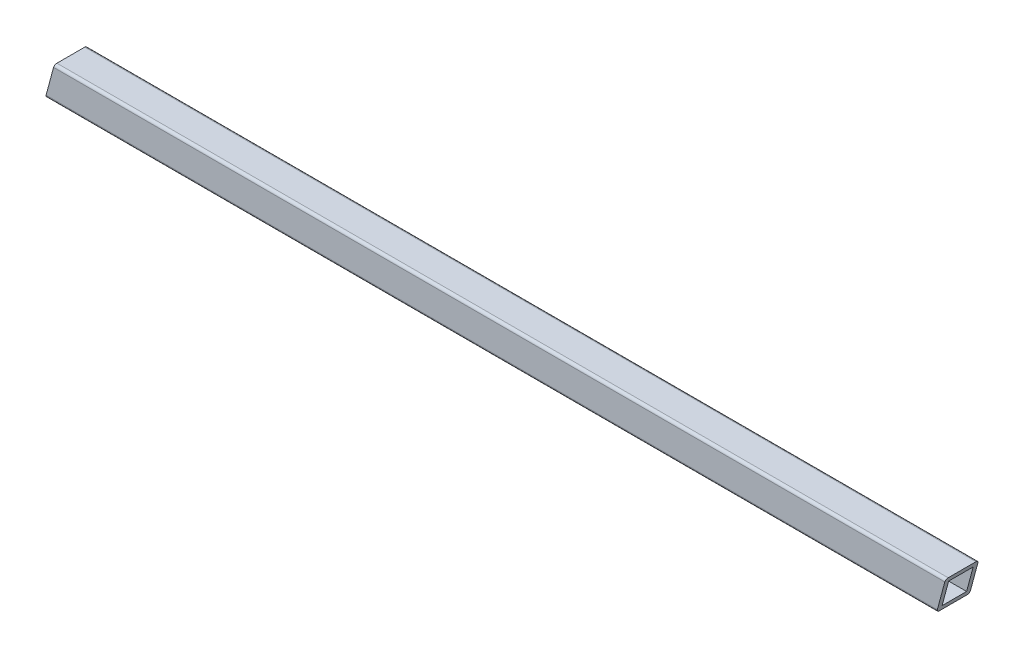
SolidWorks part; units mm, degrees
material "Plain Carbon Steel"
ref_plane "Front Plane" through (0, 0, 0) normal (0, 0, 1) x (1, 0, 0)
ref_plane "Top Plane" through (0, 0, 0) normal (0, 1, 0) x (1, 0, 0)
ref_plane "Right Plane" through (0, 0, 0) normal (1, 0, 0) x (0, 0, -1)
sketch "Sketch1" plane through (0, 0, 0) normal (1, 0, 0) x (0, 0, -1)
  line L0 (0, 2.54) -> (0, 29.21)
  line L1 (-2.54, 31.75) -> (-29.21, 31.75)
  line L2 (-31.75, 29.21) -> (-31.75, 2.54)
  line L3 (-29.21, 0) -> (-2.54, 0)
  line L4 (-4.1275, 4.1275) -> (-4.1275, 27.6225)
  line L5 (-4.1275, 27.6225) -> (-27.6225, 27.6225)
  line L6 (-27.6225, 27.6225) -> (-27.6225, 4.1275)
  line L7 (-27.6225, 4.1275) -> (-4.1275, 4.1275)
  arc A0 (-31.75, 2.54) -> (-29.21, 0) centre (-29.21, 2.54) ccw
  arc A1 (0, 2.54) -> (-2.54, 0) centre (-2.54, 2.54) cw
  arc A2 (0, 29.21) -> (-2.54, 31.75) centre (-2.54, 29.21) ccw
  arc A3 (-31.75, 29.21) -> (-29.21, 31.75) centre (-29.21, 29.21) cw
  arc A4 (-4.1275, 27.6225) -> (-4.1275, 27.6225) centre (-4.1275, 27.6225) ccw
  arc A5 (-27.6225, 27.6225) -> (-27.6225, 27.6225) centre (-27.6225, 27.6225) cw
  arc A6 (-27.6225, 4.1275) -> (-27.6225, 4.1275) centre (-27.6225, 4.1275) ccw
  arc A7 (-4.1275, 4.1275) -> (-4.1275, 4.1275) centre (-4.1275, 4.1275) cw
  point P12 (0, 0)
  point P15 (0, 31.75)
  point P18 (-31.75, 31.75)
  dimension "D3" = 2.54
  dimension "D1" = 31.75
  dimension "D2" = 31.75
  dimension "D4" = 4.1275
extrude "Boss-Extrude1" add sketch "Sketch1" along normal blind 1320.8
sketch "Sketch2" plane through (1320.8, 0, 0) normal (1, 0, 0) x (0, 0, -1)
  line L0 (-31.75, 15.875) -> (0, 15.875)
  line L1 (-31.75, 29.21) -> (-31.75, 2.54) construction
  line L2 (0, 2.54) -> (0, 29.21) construction
scale "Scale2" scale about centroid uniform scaling no x scale factor 1 y scale factor 0.4 z scale factor 0.4
sketch "Sketch3" plane through (0, 0, 22.225) normal (0, 0, 1) x (1, 0, 0)
  line L6 (877.4007, 22.225) -> (873.9977, 9.525)
  line L7 (1320.8, 22.225) -> (0, 22.225) construction
  line L9 (1320.8, 9.525) -> (0, 9.525) construction
  line L10 (877.4007, 22.225) -> (851.2664, 22.225)
  line L11 (851.2664, 22.225) -> (851.2664, 9.525)
  line L12 (851.2664, 9.525) -> (873.9977, 9.525)
  point P4 (911.3142, 22.225)
  point P5 (888.2379, 22.225)
  dimension "D1" = 75
extrude "Cut-Extrude1" cut sketch "Sketch3" against normal through all
sketch "Sketch4" plane through (0, 0, 22.225) normal (0, 0, 1) x (1, 0, 0)
  line L0 (1215.797, 9.525) -> (1320.8, 9.525)
  line L1 (1320.8, 9.525) -> (1320.8, 22.225)
  line L2 (1320.8, 22.225) -> (1219.2, 22.225)
  line L4 (1320.8, 22.225) -> (877.4007, 22.225) construction
  line L5 (1219.2, 22.225) -> (1215.797, 9.525)
  line L7 (1320.8, 9.525) -> (873.9977, 9.525) construction
  point P7 (1200.6672, 9.525)
  point P12 (1205.4139, 22.225)
  dimension "D1" = 101.6
  dimension "D2" = 105
extrude "Cut-Extrude2" cut sketch "Sketch4" against normal through all
sketch "Sketch5" plane through (0, 0, 22.225) normal (0, 0, 1) x (1, 0, 0)
  line L0 (875.6992, 15.875) -> (1217.4985, 15.875) construction
  line L1 (874.2699, 10.541) -> (877.1284, 21.209) construction
  line L2 (1218.9278, 21.209) -> (1216.0693, 10.541) construction
